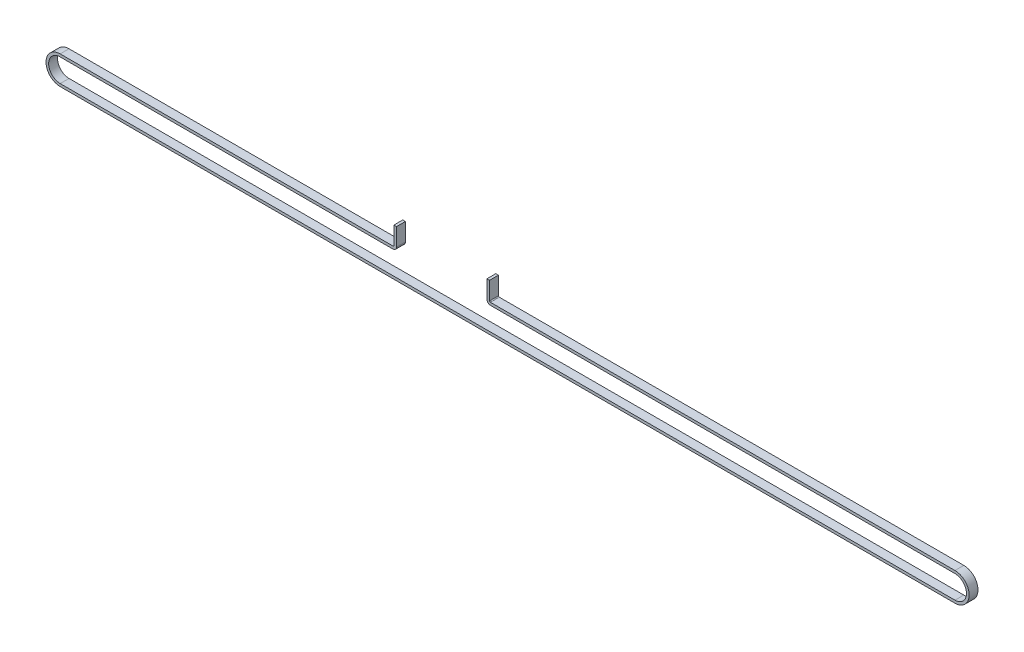
SolidWorks part; units mm, degrees
ref_plane "Front Plane" through (0, 0, 0) normal (0, 0, 1) x (1, 0, 0)
ref_plane "Top Plane" through (0, 0, 0) normal (0, 1, 0) x (1, 0, 0)
ref_plane "Right Plane" through (0, 0, 0) normal (1, 0, 0) x (0, 0, -1)
sketch "Sketch1" plane through (0, 0, 0) normal (0, 0, 1) x (1, 0, 0)
  line L0 (0, 0) -> (505, 0) construction
  line L1 (188.33, 8.5) -> (188.33, 18.5)
  line L2 (242.33, 8.5) -> (242.33, 18.5)
  line L3 (0, -6.5) -> (505, -6.5)
  line L4 (240.83, 18.5) -> (240.83, 8.5)
  line L5 (240.83, 18.5) -> (242.33, 18.5)
  line L6 (188.33, 18.5) -> (189.83, 18.5)
  line L7 (189.83, 18.5) -> (189.83, 8.5)
  line L8 (187.83, 6.5) -> (0, 6.5)
  line L9 (242.83, 6.5) -> (505, 6.5)
  line L10 (187.83, 8) -> (0, 8)
  line L11 (0, -8) -> (505, -8)
  line L12 (242.83, 8) -> (505, 8)
  arc A0 (0, 6.5) -> (0, -6.5) centre (0, 0) ccw
  arc A1 (505, -6.5) -> (505, 6.5) centre (505, 0) ccw
  arc A2 (189.83, 8.5) -> (187.83, 6.5) centre (187.83, 8.5) cw
  arc A3 (240.83, 8.5) -> (242.83, 6.5) centre (242.83, 8.5) ccw
  arc A4 (188.33, 8.5) -> (187.83, 8) centre (187.83, 8.5) cw
  arc A5 (0, 8) -> (0, -8) centre (0, 0) ccw
  arc A6 (505, -8) -> (505, 8) centre (505, 0) ccw
  arc A7 (242.33, 8.5) -> (242.83, 8) centre (242.83, 8.5) ccw
  arc A8 (188.33, 8.5) -> (187.83, 8) centre (187.83, 8.5) cw construction
  dimension "D1" = 13
  dimension "D2" = 505
  dimension "D5" = 2
  dimension "D3" = 188.33
  dimension "D4" = 262.67
  dimension "D6" = 1.5
  dimension "D7" = 10
extrude "Boss-Extrude1" add sketch "Sketch1" along normal blind 5
